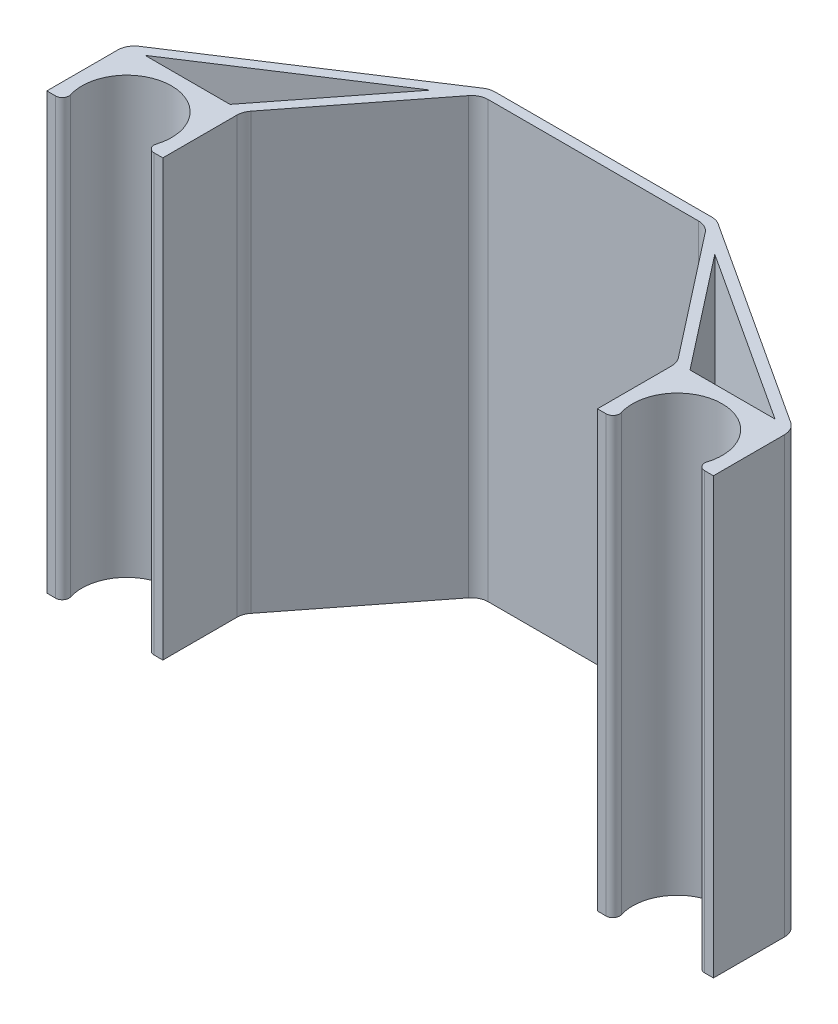
SolidWorks part; units mm, degrees
ref_plane "Front Plane" through (0, 0, 0) normal (0, 0, 1) x (1, 0, 0)
ref_plane "Top Plane" through (0, 0, 0) normal (0, 1, 0) x (1, 0, 0)
ref_plane "Right Plane" through (0, 0, 0) normal (1, 0, 0) x (0, 0, -1)
sketch "Sketch1" plane through (0, 0, 0) normal (0, 1, 0) x (1, 0, 0)
  line L0 (0, 0) -> (-34, 0)
  line L1 (-34, 0) -> (-100, -43)
  line L2 (-100, -43) -> (-100, -66.97)
  line L3 (-100, -66.97) -> (-97.3586, -66.97)
  line L4 (-67.8414, -66.97) -> (-65.2, -66.97)
  line L5 (-65.2, -66.97) -> (-65.2, -43)
  line L6 (-69.0047, -43) -> (-94.5043, -43)
  line L7 (-94.5043, -43) -> (-42.6567, -9.2205)
  line L8 (-34, -3) -> (0, -3)
  line L9 (0, -3) -> (0, 0)
  line L10 (-69.0047, -43) -> (-42.6567, -9.2205)
  line L11 (-34, -3) -> (-65.2, -43)
  arc A0 (-95.4481, -64.3784) -> (-69.7519, -64.3784) centre (-82.6, -60.4) cw
  arc A1 (-67.8414, -66.97) -> (-69.7519, -64.3784) centre (-67.8414, -64.97) cw
  arc A2 (-95.4481, -64.3784) -> (-97.3586, -66.97) centre (-97.3586, -64.97) cw
  dimension "D3" = 13.45
  dimension "D11" = 2
  dimension "D1" = 100
  dimension "D2" = 34.8
  dimension "D4" = 17.4
  dimension "D5" = 23.97
  dimension "D6" = 3
  dimension "D7" = 43
  dimension "D8" = 3
  dimension "D9" = 3
  dimension "D10" = 3
  dimension "D12" = 66
extrude "Boss-Extrude1" add sketch "Sketch1" along normal blind 130.5 contours L5 L11 L8 L9 L0 L1 L2 L3 A2 A0 A1 L4
mirror "Mirror1" about plane through (0, 130.5, 3) normal (-1, 0, 0) of "Boss-Extrude1"
fillet "Fillet1" radius 5 8 edges at (-100, 65.25, 43) (-34, 65.25, 0) (34, 65.25, 0) (100, 65.25, 43) (65.2, 65.25, 43) (34, 65.25, 3) (-34, 65.25, 3) (-65.2, 65.25, 43)
